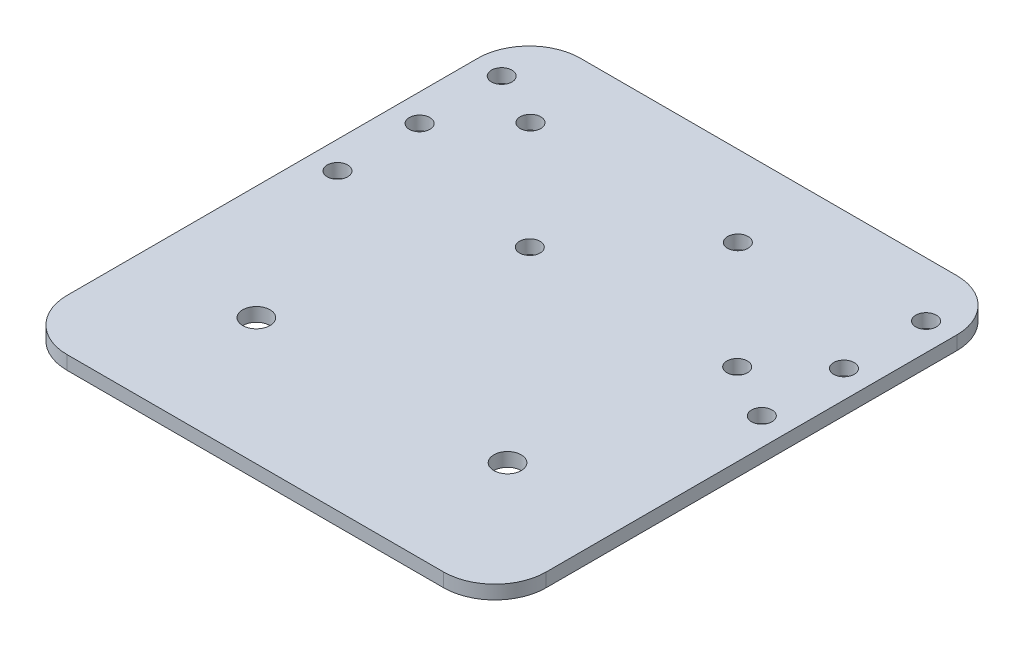
SolidWorks part; units mm, degrees
ref_plane "Front Plane" through (0, 0, 0) normal (0, 0, 1) x (1, 0, 0)
ref_plane "Top Plane" through (0, 0, 0) normal (0, 1, 0) x (1, 0, 0)
ref_plane "Right Plane" through (0, 0, 0) normal (1, 0, 0) x (0, 0, -1)
sketch "Sketch1" plane through (0, 0, 0) normal (0, 1, 0) x (1, 0, 0)
  line L0 (0, 0) -> (0, 33) construction
  line L1 (5, 0) -> (25.3, 0) construction
  line L2 (5, 0) -> (5, 33) construction
  line L3 (5, 33) -> (25.3, 33) construction
  line L4 (25.3, 0) -> (25.3, 33) construction
  line L5 (31, 36.5) -> (31, -3.5) construction
  line L6 (-5, 0) -> (-25.3, 0) construction
  line L7 (-5, 0) -> (-5, 33) construction
  line L8 (-5, 33) -> (-25.3, 33) construction
  line L9 (-25.3, 0) -> (-25.3, 33) construction
  line L14 (0, 33) -> (0, 52.3803) construction
  line L15 (35, 36.5) -> (-35, 36.5)
  line L16 (0, -13.2516) -> (0, -30.0395) construction
  line L17 (-23, -36.5) -> (23, -36.5) construction
  line L18 (-23, -36.5) -> (-23, -3.5) construction
  line L19 (-23, -3.5) -> (23, -3.5) construction
  line L20 (23, -36.5) -> (23, -3.5) construction
  line L21 (-23, -36.5) -> (23, -3.5) construction
  line L22 (-23, -3.5) -> (23, -36.5) construction
  line L23 (-35, 36.5) -> (-35, -38.5)
  line L24 (0, -30.0395) -> (0, -44.3768) construction
  line L25 (-35, -38.5) -> (35, -38.5)
  line L26 (35, 36.5) -> (35, -38.5)
  circle A0 centre (7.3, 24.7) radius 1.5
  circle A1 centre (23, 8.9) radius 1.5
  circle A2 centre (-23, 24.7) radius 1.5
  circle A3 centre (-7.3, 8.9) radius 1.5
  circle A4 centre (31, 16.5) radius 1.5
  circle A5 centre (31, 28.5) radius 1.5
  circle A6 centre (31, 4.5) radius 1.5
  circle A7 centre (-31, 28.5) radius 1.5
  circle A8 centre (-31, 16.5) radius 1.5
  circle A9 centre (-31, 4.5) radius 1.5
  circle A10 centre (18.35, -20) radius 2
  circle A12 centre (-18.35, -20) radius 2
  point P21 (0, 16.5)
  point P38 (0, -20)
  point P51 (0, 0)
  point P53 (0, -38.5)
  point P54 (0, 36.5)
  dimension "D8" = 3
  dimension "D25" = 4
  dimension "D1" = 20.3
  dimension "D2" = 33
  dimension "D3" = 8.9
  dimension "D4" = 8.3
  dimension "D5" = 2.3
  dimension "D6" = 2.3
  dimension "D7" = 5
  dimension "D9" = 20.3
  dimension "D10" = 33
  dimension "D11" = 5
  dimension "D12" = 2.3
  dimension "D13" = 8.3
  dimension "D14" = 2.3
  dimension "D15" = 8.9
  dimension "D16" = 35
  dimension "D17" = 75
  dimension "D18" = 36.5
  dimension "D19" = 12
  dimension "D20" = 12
  dimension "D21" = 33
  dimension "D22" = 46
  dimension "D24" = 36.7
extrude "Boss-Extrude1" add sketch "Sketch1" along normal blind 2
fillet "Fillet2" radius 7.5 4 edges at (35, 1, 38.5) (-35, 1, 38.5) (35, 1, -36.5) (-35, 1, -36.5)
